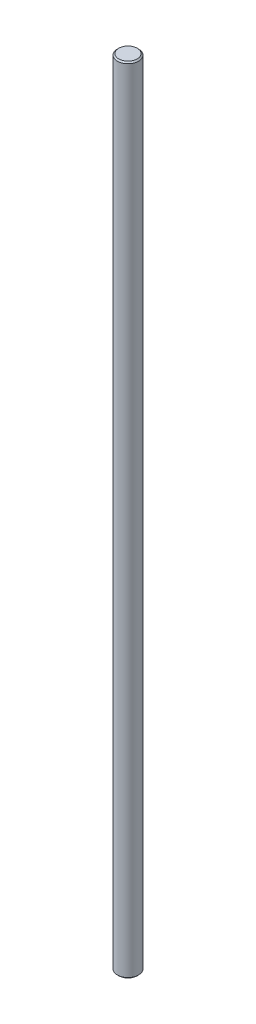
SolidWorks part; units mm, degrees
ref_plane "Front Plane" through (0, 0, 0) normal (0, 0, 1) x (1, 0, 0)
ref_plane "Top Plane" through (0, 0, 0) normal (0, 1, 0) x (1, 0, 0)
ref_plane "Right Plane" through (0, 0, 0) normal (1, 0, 0) x (0, 0, -1)
sketch "Sketch1" plane through (0, 0, 0) normal (0, 1, 0) x (1, 0, 0)
  circle A0 centre (0, 0) radius 4
  dimension "D1" = 8
extrude "Boss-Extrude1" add sketch "Sketch1" along normal mid plane 300
chamfer "Chamfer1" distance 0.5 angle 45 2 edges at (0, -150, 4) (0, 150, 4)
